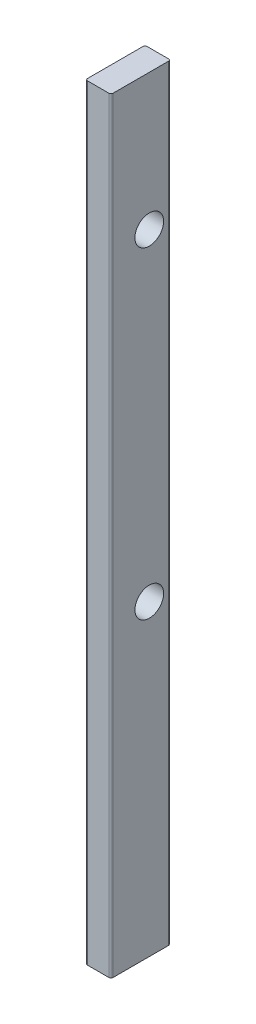
SolidWorks part; units mm, degrees
ref_plane "Front" through (0, 0, 0) normal (0, 0, 1) x (1, 0, 0)
ref_plane "Top" through (0, 0, 0) normal (0, 1, 0) x (1, 0, 0)
ref_plane "Right" through (0, 0, 0) normal (1, 0, 0) x (0, 0, -1)
sketch "Sketch1" plane through (0, 0, 0) normal (0, 1, 0) x (1, 0, 0)
  line L1 (-19.05, -44.45) -> (19.05, -44.45)
  line L2 (-19.05, -44.45) -> (-19.05, 44.45)
  line L3 (-19.05, 44.45) -> (19.05, 44.45)
  line L5 (-19.05, -44.45) -> (19.05, 44.45) construction
  line L6 (-19.05, 44.45) -> (19.05, -44.45) construction
  line L7 (19.05, 34.3752) -> (19.05, 44.45) construction
  line L8 (19.05, -44.45) -> (19.05, 44.45)
  line L9 (17.4625, 44.45) -> (19.05, 44.45) construction
  point P0 (0, 0)
  dimension "D1" = 38.1
  dimension "D2" = 88.9
extrude "Boss-Extrude1" add sketch "Sketch1" along normal blind 1143
sketch "Sketch2" plane through (-19.05, 0, 0) normal (1, 0, 0) x (0, 0, -1)
  line L0 (44.45, 0) -> (-44.45, 0) construction
  line L1 (44.45, 1143) -> (44.45, 0) construction
  circle A0 centre (12.7, 458.7875) radius 21.4313
  circle A1 centre (12.7, 939.8) radius 21.4313
  dimension "D1" = 42.8625
  dimension "D2" = 31.75
  dimension "D4" = 481.0125
  dimension "D3" = 458.7875
extrude "Cut-Extrude4" cut sketch "Sketch2" along normal through all
fillet "Fillet1" radius 3.175 4 edges at (19.05, 571.5, 44.45) (-19.05, 571.5, 44.45) (-19.05, 571.5, -44.45) (19.05, 571.5, -44.45)
